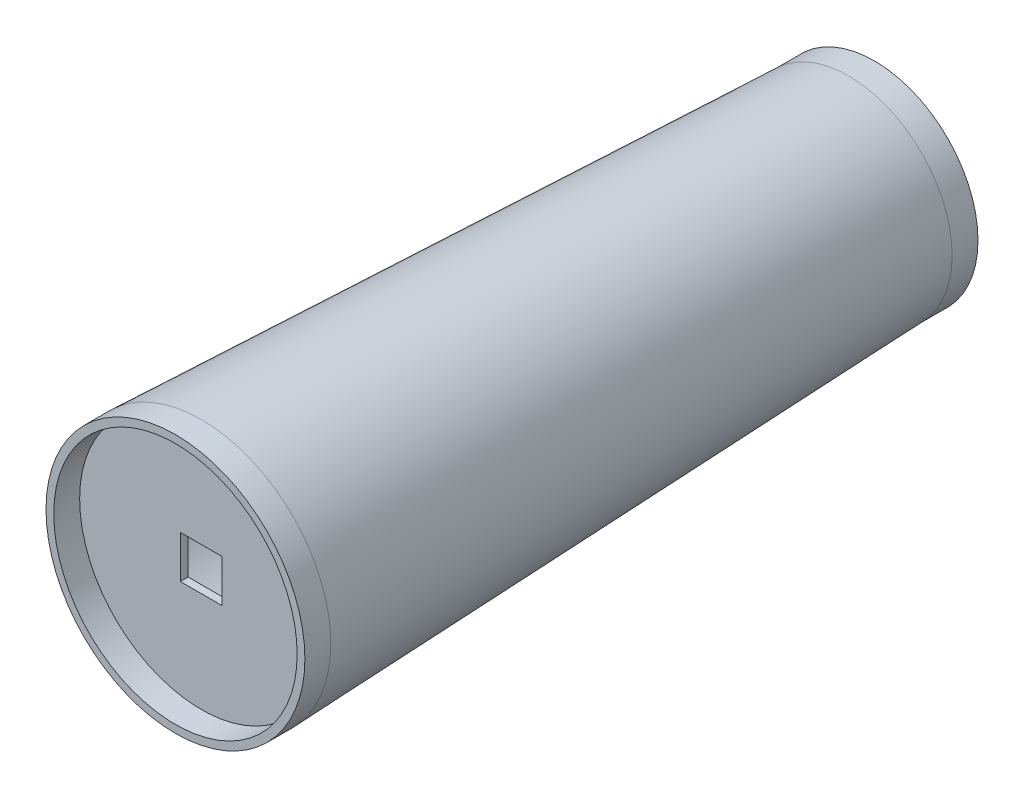
SolidWorks part; units mm, degrees
ref_plane "Front Plane" through (0, 0, 0) normal (0, 0, 1) x (1, 0, 0)
ref_plane "Top Plane" through (0, 0, 0) normal (0, 1, 0) x (1, 0, 0)
ref_plane "Right Plane" through (0, 0, 0) normal (1, 0, 0) x (0, 0, -1)
sketch "Sketch1" plane through (0, 0, 0) normal (1, 0, 0) x (0, 0, -1)
  line L0 (0, 0) -> (3, 0)
  line L1 (250, 0) -> (250, 40)
  line L2 (250, 40) -> (0, 50)
  line L3 (0, 50) -> (0, 0)
  line L4 (3, 0) -> (3, 47)
  line L5 (3, 47) -> (247, 37.24)
  line L6 (247, 37.24) -> (247, 0)
  line L7 (247, 0) -> (250, 0)
  dimension "D1" = 50
  dimension "D2" = 40
  dimension "D3" = 250
  dimension "D4" = 47
  dimension "D5" = 3
  dimension "D6" = 3
sketch "Sketch2" plane through (0, 0, 0) normal (0, 0, 1) x (1, 0, 0)
  circle A0 centre (0, 0) radius 50
  circle A1 centre (0, 0) radius 47
  dimension "D1" = 100
  dimension "D2" = 94
ref_plane "Plane1" through (0, 0, -250) normal (0, 0, 1) x (1, 0, 0)
sketch "Sketch3" plane through (0, 0, -250) normal (0, 0, 1) x (1, 0, 0)
  circle A1 centre (0, 0) radius 40
  circle A2 centre (0, 0) radius 37
  dimension "D1" = 80
  dimension "D2" = 74
revolve "Revolve1" add sketch "Sketch1" angle 360 about L0
extrude "Boss-Extrude2" add sketch "Sketch2" along normal blind 10
sketch "Sketch4" plane through (0, 0, 0) normal (0, 0, 1) x (1, 0, 0)
  line L1 (-8.075, 8.215) -> (8.075, 8.215)
  line L2 (-8.075, 8.215) -> (-8.075, -8.215)
  line L3 (-8.075, -8.215) -> (8.075, -8.215)
  line L4 (8.075, 8.215) -> (8.075, -8.215)
  line L5 (-8.075, 8.215) -> (8.075, -8.215) construction
  line L6 (-8.075, -8.215) -> (8.075, 8.215) construction
  point P0 (0, 0)
  dimension "D1" = 16.15
  dimension "D2" = 16.43
extrude "Cut-Extrude1" cut sketch "Sketch4" against normal blind 10
extrude "Boss-Extrude3" add sketch "Sketch3" against normal blind 10
